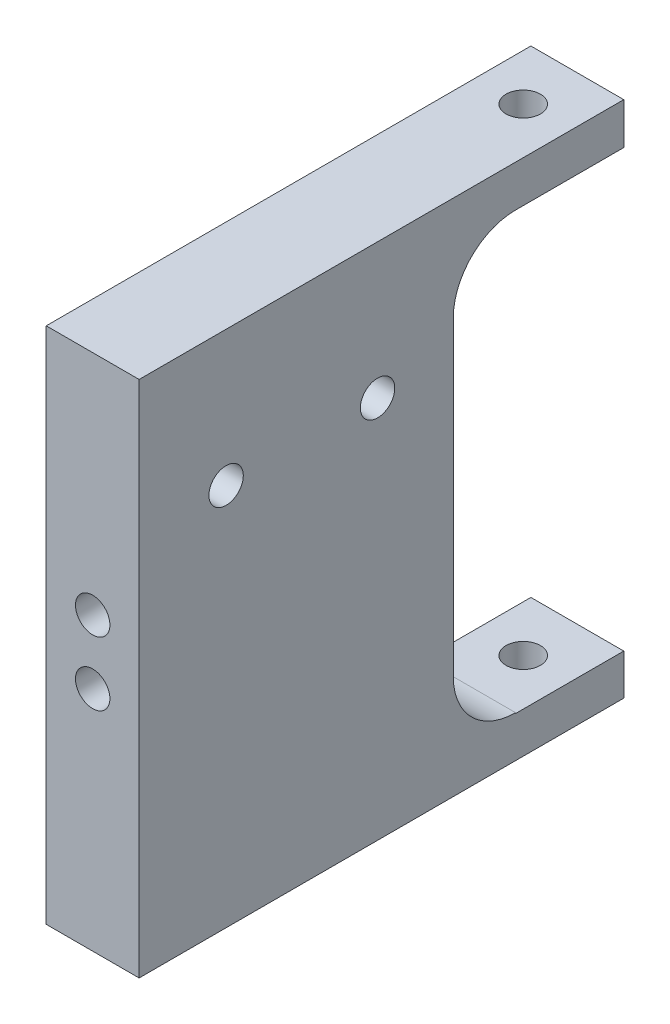
SolidWorks part; units mm, degrees
material "Beech"
ref_plane "Front Plane" through (0, 0, 0) normal (0, 0, 1) x (1, 0, 0)
ref_plane "Top Plane" through (0, 0, 0) normal (0, 1, 0) x (1, 0, 0)
ref_plane "Right Plane" through (0, 0, 0) normal (1, 0, 0) x (0, 0, -1)
ref_plane "Plane1" through (27.9534, 0, 0) normal (1, 0, 0) x (0, 0, -1)
sketch "Sketch1" plane through (27.9534, 0, 0) normal (1, 0, 0) x (0, 0, -1)
  line L0 (12.7, -49.4365) -> (12.7, 11.4194)
  line L1 (12.7, 11.4194) -> (-28.956, 11.4194)
  line L2 (-28.956, 11.4194) -> (-28.956, -49.4365)
  line L3 (-28.956, -49.4365) -> (12.7, -49.4365)
extrude "Boss-Extrude1" add sketch "Sketch1" against normal blind 10.9059
sketch "Sketch2" plane through (17.0475, 0, 0) normal (-1, 0, 0) x (0, 0, 1)
  line L0 (-12.7, 6.543) -> (-12.7, -44.643)
  line L1 (-12.7, -44.643) -> (0, -44.643)
  line L2 (0, -44.643) -> (0, -44.5602)
  line L3 (7.3152, -37.245) -> (7.3152, -0.7722)
  line L4 (0, 6.543) -> (-12.7, 6.543)
  arc A0 (0, -44.5602) -> (7.3152, -37.245) centre (0, -37.245) ccw
  arc A1 (7.3152, -0.7722) -> (0, 6.543) centre (0, -0.7722) ccw
extrude "Cut-Extrude1" cut sketch "Sketch2" against normal through all
ref_plane "Plane2" through (0, 0, 19.1255) normal (0, 0, -1) x (-1, 0, 0)
sketch "Sketch3" plane through (0, 0, 19.1255) normal (0, 0, -1) x (-1, 0, 0)
  line L0 (-27.9534, -3.5337) -> (-27.9534, -5.553)
  line L1 (-27.9534, -5.553) -> (-17.0475, -5.553)
  line L2 (-17.0475, -5.553) -> (-17.0475, -3.5337)
  line L3 (-17.0475, -3.5337) -> (-27.9534, -3.5337)
  line L4 (-27.9534, -5.553) -> (-17.0475, -5.553) construction
sketch "Sketch4" plane through (0, 0, 19.1255) normal (0, 0, -1) x (-1, 0, 0)
  line L0 (-27.9534, 3.9618) -> (-27.9534, 1.9425)
  line L1 (-27.9534, 1.9425) -> (-17.0475, 1.9425)
  line L2 (-17.0475, 1.9425) -> (-17.0475, 3.9618)
  line L3 (-17.0475, 3.9618) -> (-27.9534, 3.9618)
  line L4 (-27.9534, 1.9425) -> (-17.0475, 1.9425) construction
ref_plane "Plane3" through (0, 0, -6.35) normal (0, 0, -1) x (-1, 0, 0)
sketch "Sketch5" plane through (0, 0, -6.35) normal (0, 0, -1) x (-1, 0, 0)
  line L0 (-24.5197, -49.4365) -> (-22.5004, -49.4365)
  line L1 (-22.5004, -49.4365) -> (-22.5004, 11.4194)
  line L2 (-22.5004, 11.4194) -> (-24.5197, 11.4194)
  line L3 (-24.5197, 11.4194) -> (-24.5197, -49.4365)
  line L4 (-22.5004, -49.4365) -> (-22.5004, 11.4194) construction
revolve "Cut-Revolve3" cut sketch "Sketch5" angle 360 about L4
ref_plane "Plane4" through (0, -22.7567, 0) normal (0, 1, 0) x (1, 0, 0)
sketch "Sketch6" plane through (0, -22.7567, 0) normal (0, 1, 0) x (1, 0, 0)
  line L0 (24.5197, -16.256) -> (22.5004, -16.256)
  line L1 (22.5004, -16.256) -> (22.5004, -28.956)
  line L2 (22.5004, -28.956) -> (24.5197, -28.956)
  line L3 (24.5197, -28.956) -> (24.5197, -16.256)
  line L4 (22.5004, -16.256) -> (22.5004, -28.956) construction
revolve "Cut-Revolve4" cut sketch "Sketch6" angle 360 about L4
ref_plane "Plane5" through (0, -15.2605, 0) normal (0, 1, 0) x (1, 0, 0)
sketch "Sketch7" plane through (0, -15.2605, 0) normal (0, 1, 0) x (1, 0, 0)
  line L0 (24.5197, -16.256) -> (22.5004, -16.256)
  line L1 (22.5004, -16.256) -> (22.5004, -28.956)
  line L2 (22.5004, -28.956) -> (24.5197, -28.956)
  line L3 (24.5197, -28.956) -> (24.5197, -16.256)
  line L4 (22.5004, -16.256) -> (22.5004, -28.956) construction
revolve "Cut-Revolve5" cut sketch "Sketch7" angle 360 about L4
sketch "Sketch8" plane through (0, 0, 28.956) normal (0, 0, 1) x (1, 0, 0)
  line L0 (17.0475, 11.4194) -> (27.9534, 11.4194)
  line L1 (27.9534, -49.4365) -> (17.0475, -49.4365)
  line L4 (27.9534, -49.4365) -> (27.9534, 11.4194)
  line L5 (27.9534, 11.4194) -> (17.0475, 11.4194)
  line L6 (17.0475, 11.4194) -> (17.0475, -49.4365)
  line L7 (17.0475, -49.4365) -> (27.9534, -49.4365)
  line L8 (27.9534, -49.4365) -> (27.9534, 11.4194)
  line L9 (27.9534, 11.4194) -> (17.0475, 11.4194)
  line L10 (17.0475, 11.4194) -> (17.0475, -49.4365)
  line L11 (17.0475, -49.4365) -> (27.9534, -49.4365)
  circle A0 centre (22.5004, -22.7567) radius 2.0193 construction
  circle A1 centre (22.5004, -15.2605) radius 2.0193 construction
  circle A2 centre (22.5004, -22.7567) radius 2.0193
  circle A3 centre (22.5004, -15.2605) radius 2.0193
  circle M5 centre (22.5004, -15.2605) radius 2.0193
  circle M6 centre (22.5004, -22.7567) radius 2.0193
  line M7 (27.9534, -49.4365) -> (27.9534, 11.4194)
  line M8 (27.9534, 11.4194) -> (17.0475, 11.4194)
  line M9 (17.0475, 11.4194) -> (17.0475, -49.4365)
  line M10 (17.0475, -49.4365) -> (27.9534, -49.4365)
  dimension "D1" = 0
extrude "Boss-Extrude2" add sketch "Sketch8" along normal blind 15.24 contours M10 M7 M8 M9 M6 M5
sketch "Sketch9" plane through (27.9534, 0, 0) normal (1, 0, 0) x (0, 0, -1)
  line L2 (12.7, 11.4194) -> (-44.196, 11.4194) construction
  line L3 (-7.3152, -37.245) -> (-7.3152, -0.7722) construction
  line L4 (-44.196, -49.4365) -> (12.7, -49.4365) construction
  circle A0 centre (-33.9852, -4.4659) radius 2.0193
  circle A1 centre (-16.2052, -4.4659) radius 2.0193
  dimension "D1" = 17.78
  dimension "D2" = 15.8853
  dimension "D3" = 8.89
  dimension "D4" = 4.0386
  dimension "D5" = 44.9706
extrude "Cut-Extrude2" cut sketch "Sketch9" against normal through all
